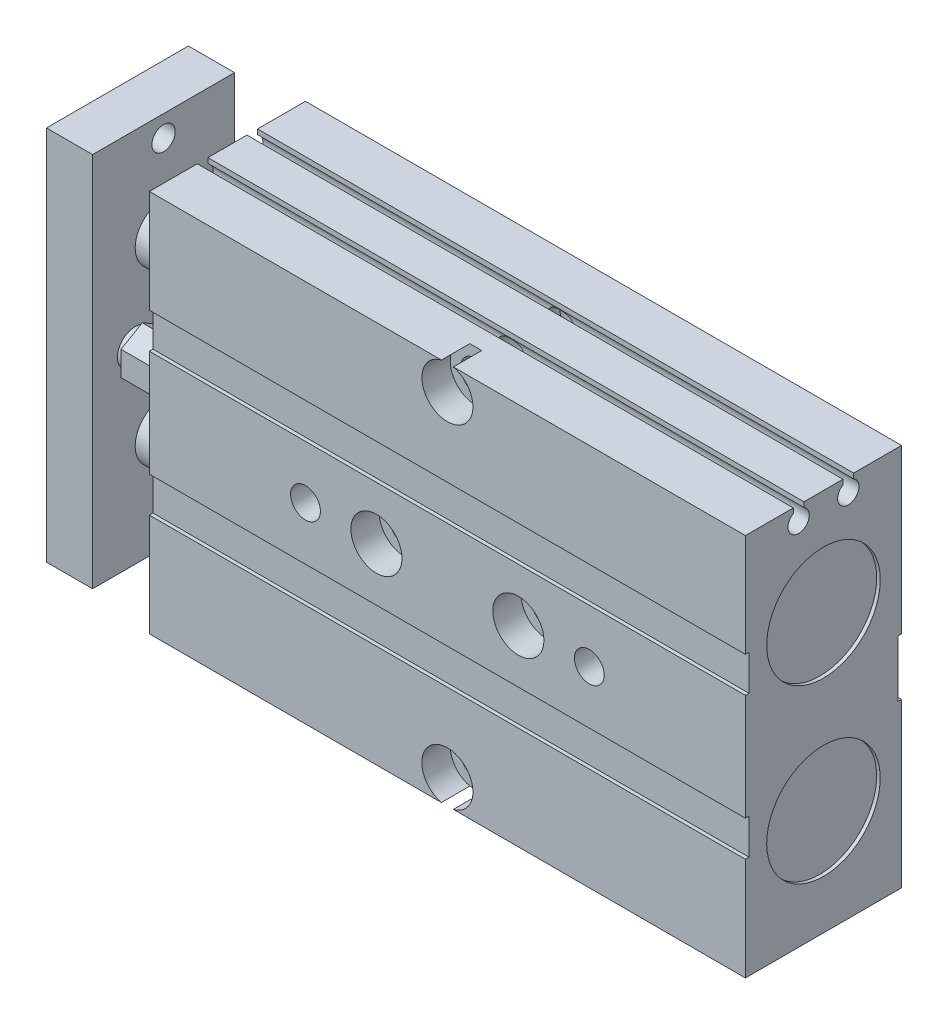
SolidWorks part; units mm, degrees
ref_plane "前视基准面" through (0, 0, 0) normal (0, 0, 1) x (1, 0, 0)
ref_plane "上视基准面" through (0, 0, 0) normal (0, 1, 0) x (1, 0, 0)
ref_plane "右视基准面" through (0, 0, 0) normal (1, 0, 0) x (0, 0, -1)
sketch "草图1" plane through (0, 0, 0) normal (0, 0, 1) x (1, 0, 0)
  line L1 (0, 0) -> (84, 0)
  line L2 (0, 0) -> (0, 54)
  line L3 (0, 54) -> (84, 54)
  line L4 (84, 0) -> (84, 54)
  dimension "D1" = 84
  dimension "D2" = 54
extrude "凸台-拉伸1" add sketch "草图1" along normal blind 22
sketch "草图2" plane through (0, 0, 0) normal (-1, 0, 0) x (0, 0, 1)
  line L0 (11, 54) -> (11, 0) construction
  line L1 (18, 25.2679) -> (18, 28.7321)
  line L2 (18, 28.7321) -> (15, 30.4641)
  line L3 (15, 30.4641) -> (12, 28.7321)
  line L4 (12, 28.7321) -> (12, 25.2679)
  line L5 (12, 25.2679) -> (15, 23.5359)
  line L6 (15, 23.5359) -> (18, 25.2679)
  line L7 (22, 54) -> (0, 54) construction
  line L8 (22, 0) -> (0, 0) construction
  line L9 (22, 27) -> (1.1064, 27) construction
  line L10 (22, 54) -> (22, 0) construction
  circle A0 centre (15, 27) radius 3 construction
  dimension "D1" = 4
  dimension "D2" = 3
extrude "凸台-拉伸2" add sketch "草图2" along normal blind 4 separate body
sketch "草图4" plane through (-4, 0, 0) normal (-1, 0, 0) x (0, 0, 1)
  line L0 (13.5, 29.5981) -> (16.5, 24.4019) construction
  line L1 (15, 30.4641) -> (12, 28.7321) construction
  line L2 (15, 23.5359) -> (18, 25.2679) construction
  line L3 (12, 25.2679) -> (15, 23.5359) construction
  line L4 (18, 25.2679) -> (18, 28.7321)
  line L5 (18, 28.7321) -> (15, 30.4641)
  line L6 (15, 30.4641) -> (12, 28.7321)
  line L7 (12, 28.7321) -> (12, 25.2679)
  line L8 (12, 25.2679) -> (15, 23.5359)
  line L9 (15, 23.5359) -> (18, 25.2679)
  line L10 (18, 25.2679) -> (18, 28.7321) construction
  circle A0 centre (15, 27) radius 3 construction
extrude "凸台-拉伸3" add sketch "草图4" along normal blind 4 separate body
sketch "草图5" plane through (0, 0, 0) normal (-1, 0, 0) x (0, 0, 1)
  line L0 (0, 27) -> (22, 27) construction
  line L1 (0, 54) -> (0, 0) construction
  line L2 (22, 54) -> (22, 0) construction
  line L3 (11, 54) -> (11, 0) construction
  line L4 (22, 54) -> (0, 54) construction
  line L5 (22, 0) -> (0, 0) construction
  circle A0 centre (11, 39.1) radius 8
  circle A1 centre (11, 14.9) radius 8
  dimension "D1" = 16
  dimension "D2" = 24.2
extrude "切除-拉伸1" cut sketch "草图5" against normal blind 0.5
sketch "草图6" plane through (84, 0, 0) normal (1, 0, 0) x (0, 0, -1)
  line L0 (-22, 27) -> (0, 27) construction
  line L1 (-22, 0) -> (-22, 54) construction
  line L2 (0, 0) -> (0, 54) construction
  line L3 (-11, 54) -> (-11, 0) construction
  line L4 (-22, 54) -> (0, 54) construction
  line L5 (-22, 0) -> (0, 0) construction
  circle A0 centre (-11, 39.1) radius 8
  circle A1 centre (-11, 14.9) radius 8
  dimension "D1" = 16
  dimension "D2" = 24.2
extrude "切除-拉伸2" cut sketch "草图6" against normal blind 0.5
sketch "草图7" plane through (0.5, 0, 0) normal (-1, 0, 0) x (0, 0, 1)
  circle A0 centre (11, 39.1) radius 4
  circle A1 centre (11, 14.9) radius 4
  dimension "D1" = 8
extrude "凸台-拉伸4" add sketch "草图7" along normal blind 9.5
sketch "草图8" plane through (-9, 0, 0) normal (-1, 0, 0) x (0, 0, 1)
  line L0 (11, 0) -> (11, 54) construction
  line L1 (1, 53.5) -> (21, 53.5)
  line L2 (1, 53.5) -> (1, 0.5)
  line L3 (1, 0.5) -> (21, 0.5)
  line L4 (21, 53.5) -> (21, 0.5)
  line L5 (22, 0) -> (0, 0) construction
  line L6 (22, 54) -> (0, 54) construction
  line L7 (0, 27) -> (22, 27) construction
  line L8 (0, 54) -> (0, 0) construction
  line L9 (22, 54) -> (22, 0) construction
  dimension "D1" = 1
  dimension "D2" = 0.5
extrude "凸台-拉伸5" add sketch "草图8" along normal blind 6.5
sketch "草图9" plane through (-9, 0, 0) normal (1, 0, 0) x (0, 0, -1)
  line L0 (-21, 27) -> (-0.5595, 27) construction
  line L1 (-21, 0.5) -> (-21, 53.5) construction
  circle A0 centre (-15, 27) radius 2.5
  dimension "D1" = 5
  dimension "D2" = 6
extrude "凸台-拉伸6" add sketch "草图9" along normal blind 1
hole_wizard "M4 螺纹孔2" positions "草图12" profile "草图11" tap size "M4" standard "ISO"
sketch "草图12" plane through (-15.5, 0, 0) normal (-1, 0, 0) x (0, 0, 1)
  line L0 (1, 27) -> (21, 27) construction
  line L1 (1, 53.5) -> (1, 0.5) construction
  line L2 (21, 0.5) -> (21, 53.5) construction
  line L3 (11, 53.5) -> (11, 0.5) construction
  line L4 (21, 53.5) -> (1, 53.5) construction
  line L5 (1, 0.5) -> (21, 0.5) construction
  point P0 (11, 50.5)
  point P1 (11, 3.5)
  dimension "D1" = 47
sketch "草图11" plane through (-15.5, 50.5, 11) normal (0, 1, 0) x (0, 0, 1)
  line L0 (0, 0) -> (0, 11.0914)
  line L1 (0, 11.0914) -> (1.65, 10.1)
  line L2 (1.65, 10.1) -> (1.65, 0)
  line L5 (1.65, 0) -> (0, 0)
  line L10 (0, 11.0914) -> (-1.65, 10.1) construction
  line L11 (0, -6.35) -> (0, 107.95) construction
  dimension "螺纹孔钻头直径" = 3.3
  dimension "螺纹孔钻头深度" = 10.1
  dimension "导头角度" = 118
cosmetic thread "孔螺蚊线1" parameters "D1"=6.5, "D2"=4
cosmetic thread "孔螺蚊线2" parameters "D1"=6.5, "D2"=4
sketch "草图13" plane through (84, 0, 0) normal (1, 0, 0) x (0, 0, -1)
  line L0 (-11, 54) -> (-11, 37.5575) construction
  line L1 (-22, 54) -> (0, 54) construction
  circle A0 centre (-14.5, 52) radius 1.5
  circle A1 centre (-7.5, 52) radius 1.5
  dimension "D1" = 3
  dimension "D2" = 7
  dimension "D3" = 2
extrude "切除-拉伸3" cut sketch "草图13" against normal up to surface (84 mm away) up to face at (0, 14.9, 3)
sketch "草图14" plane through (84, 0, 0) normal (1, 0, 0) x (0, 0, -1)
  line L0 (-22, 54) -> (0, 54) construction
  line L1 (-15.25, 54) -> (-13.75, 54)
  line L2 (-15.25, 54) -> (-15.25, 52)
  line L3 (-15.25, 52) -> (-13.75, 52)
  line L4 (-13.75, 54) -> (-13.75, 52)
  line L5 (-11, 54) -> (-11, 38.5062) construction
  line L6 (-14.5, 52) -> (-14.5, 42.9315) construction
  line L7 (-8.25, 54) -> (-8.25, 52)
  line L8 (-6.75, 52) -> (-8.25, 52)
  line L9 (-6.75, 54) -> (-6.75, 52)
  line L10 (-6.75, 54) -> (-8.25, 54)
  dimension "D1" = 2
  dimension "D2" = 1.5
extrude "切除-拉伸4" cut sketch "草图14" against normal up to surface (84 mm away) up to face at (0, 52, 6)
hole_wizard "M5 螺纹孔1" positions "草图16" profile "草图15" tap size "M5" standard "ISO"
sketch "草图16" plane through (0, 0, 0) normal (0, -1, 0) x (1, 0, 0)
  line L0 (84, 11) -> (0, 11) construction
  line L1 (84, 22) -> (84, 0) construction
  line L2 (0, 22) -> (0, 0) construction
  line L3 (0, 15) -> (0, 18) construction
  point P0 (15.5, 12)
  point P1 (68.5, 12)
  dimension "D1" = 1
  dimension "D2" = 15.5
  dimension "D3" = 15.5
sketch "草图15" plane through (15.5, 0, 12) normal (1, 0, 0) x (0, 0, -1)
  line L0 (0, 0) -> (0, 13.6618)
  line L1 (0, 13.6618) -> (2.1, 12.4)
  line L2 (2.1, 12.4) -> (2.1, 0)
  line L5 (2.1, 0) -> (0, 0)
  line L10 (0, 13.6618) -> (-2.1, 12.4) construction
  line L11 (0, -6.35) -> (0, 107.95) construction
  dimension "螺纹孔钻头直径" = 4.2
  dimension "螺纹孔钻头深度" = 12.4
  dimension "导头角度" = 118
cosmetic thread "孔螺蚊线3" parameters "D1"=10, "D2"=5
cosmetic thread "孔螺蚊线4" parameters "D1"=10, "D2"=5
sketch "草图17" plane through (0, 0, 0) normal (-1, 0, 0) x (0, 0, 1)
  line L0 (0, 54) -> (0, 0) construction
  line L1 (0, 31) -> (0.5, 31)
  line L2 (0, 31) -> (0, 23)
  line L3 (0, 23) -> (0.5, 23)
  line L4 (0.5, 31) -> (0.5, 23)
  line L5 (22, 54) -> (22, 0) construction
  line L6 (22, 39.5) -> (21.5, 39.5)
  line L7 (22, 39.5) -> (22, 34.5)
  line L8 (22, 34.5) -> (21.5, 34.5)
  line L9 (21.5, 39.5) -> (21.5, 34.5)
  line L10 (22, 27) -> (0, 27) construction
  line L11 (21.5, 14.5) -> (21.5, 19.5)
  line L12 (22, 19.5) -> (21.5, 19.5)
  line L13 (22, 14.5) -> (22, 19.5)
  line L14 (22, 14.5) -> (21.5, 14.5)
  line L15 (21.5, 17) -> (22, 17) construction
  line L16 (21.5, 37) -> (22, 37) construction
  dimension "D1" = 0.5
  dimension "D2" = 8
  dimension "D3" = 20
  dimension "D4" = 5
  dimension "D5" = 0.5
extrude "切除-拉伸5" cut sketch "草图17" against normal up to surface (84 mm away) up to face at (84, 44.2998, 11)
hole_wizard "M5 螺纹孔2" positions "草图19" profile "草图18" tap size "M5" standard "ISO"
sketch "草图19" plane through (0, 0, 22) normal (0, 0, 1) x (1, 0, 0)
  line L0 (42, 54) -> (42, 0) construction
  line L1 (84, 54) -> (0, 54) construction
  line L2 (0, 0) -> (84, 0) construction
  line L3 (84, 27) -> (0, 27) construction
  line L4 (84, 19.5) -> (84, 34.5) construction
  line L5 (0, 34.5) -> (0, 19.5) construction
  point P0 (22, 27)
  point P1 (62, 27)
  dimension "D1" = 40
sketch "草图18" plane through (22, 27, 22) normal (1, 0, 0) x (0, -1, 0)
  line L0 (0, 0) -> (0, 13.6618)
  line L1 (0, 13.6618) -> (2.1, 12.4)
  line L2 (2.1, 12.4) -> (2.1, 0)
  line L5 (2.1, 0) -> (0, 0)
  line L10 (0, 13.6618) -> (-2.1, 12.4) construction
  line L11 (0, -6.35) -> (0, 107.95) construction
  dimension "螺纹孔钻头直径" = 4.2
  dimension "螺纹孔钻头深度" = 12.4
  dimension "导头角度" = 118
cosmetic thread "孔螺蚊线5" parameters "D1"=10, "D2"=5
cosmetic thread "孔螺蚊线6" parameters "D1"=10, "D2"=5
hole_wizard "M4 六角凹头螺钉的柱形沉头孔1" positions "草图21" profile "草图20" counterbore size "M4" standard "ISO" end condition through all
sketch "草图21" plane through (0, 0, 22) normal (0, 0, 1) x (1, 0, 0)
  line L0 (0, 27) -> (84, 27) construction
  line L1 (0, 34.5) -> (0, 19.5) construction
  line L2 (84, 19.5) -> (84, 34.5) construction
  line L3 (42, 0) -> (42, 54) construction
  line L4 (0, 0) -> (84, 0) construction
  line L5 (84, 54) -> (0, 54) construction
  point P0 (32, 27)
  point P2 (42, 50.5)
  point P4 (42, 3.5)
  point P6 (52, 27)
  dimension "D1" = 32
  dimension "D2" = 47
  dimension "D3" = 20
sketch "草图20" plane through (32, 27, 22) normal (1, 0, 0) x (0, -1, 0)
  line L0 (0, 0) -> (0, 22)
  line L1 (0, 22) -> (2.15, 22)
  line L3 (2.15, 22) -> (2.15, 4)
  line L4 (2.15, 4) -> (3.6, 4)
  line L5 (3.6, 4) -> (3.6, 0)
  line L7 (3.6, 0) -> (0, 0)
  line L11 (0, -6.35) -> (0, 107.95) construction
  dimension "通孔孔直径" = 4.3
  dimension "通孔孔深度" = 22
  dimension "柱形沉头孔直径" = 7.2
  dimension "柱形沉头孔深度" = 4
sketch "草图22" plane through (0, 0, 0) normal (0, 0, -1) x (-1, 0, 0)
  circle A0 centre (-42, 50.5) radius 3.25
  circle A1 centre (-32, 27) radius 3.25
  circle A2 centre (-52, 27) radius 3.25
  circle A3 centre (-42, 3.5) radius 3.25
  dimension "D1" = 6.5
extrude "切除-拉伸10" cut sketch "草图22" against normal blind 4
